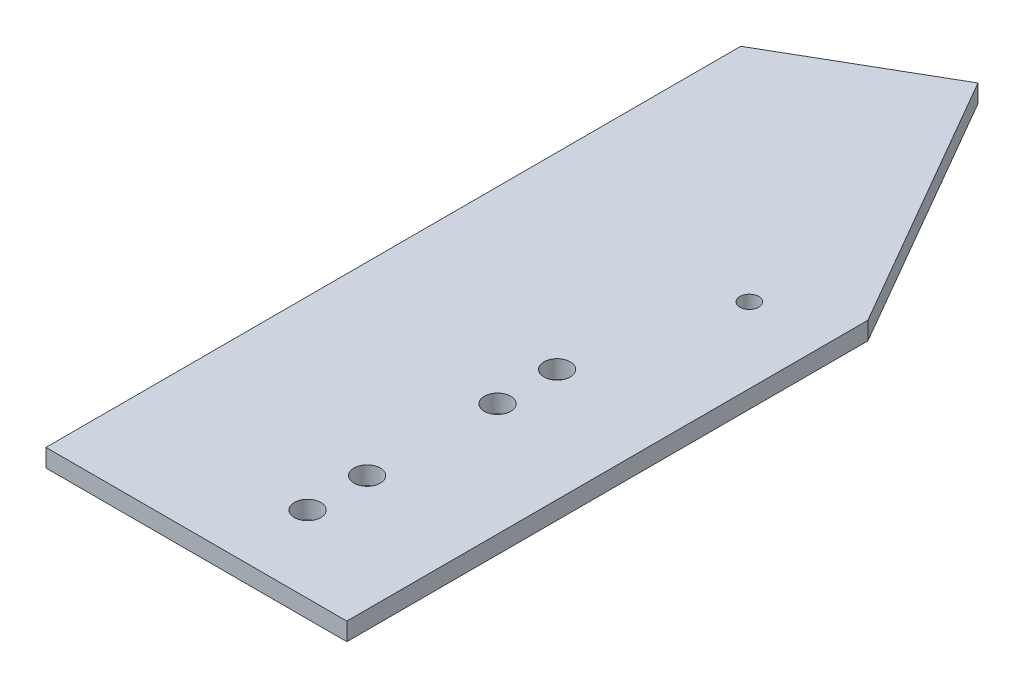
SolidWorks part; units mm, degrees
ref_plane "Front Plane" through (0, 0, 0) normal (0, 0, 1) x (1, 0, 0)
ref_plane "Top Plane" through (0, 0, 0) normal (0, 1, 0) x (1, 0, 0)
ref_plane "Right Plane" through (0, 0, 0) normal (1, 0, 0) x (0, 0, -1)
sketch "Sketch1" plane through (0, 0, 0) normal (0, 1, 0) x (1, 0, 0)
  line L10 (-100, 55.5) -> (-100, 90.144)
  line L11 (-100, 90.144) -> (-110, 107.464)
  line L12 (-110, 107.464) -> (-120, 101.691)
  line L13 (-120, 101.691) -> (-120, 55.5)
  line L14 (-120, 55.5) -> (-100, 55.5)
  circle A2 centre (-107.7, 64.55) radius 0.875
  circle A4 centre (-107.5, 76.98) radius 0.875
  circle A6 centre (-107.7, 60.59) radius 0.875
  circle A8 centre (-105, 87.26) radius 0.625
  circle A10 centre (-107.5, 73.02) radius 0.875
extrude "Boss-Extrude1" add sketch "Sketch1" along normal blind 1.19 contours L13 L14 L10 L11 L12 A10 A8 A6 A4 A2
